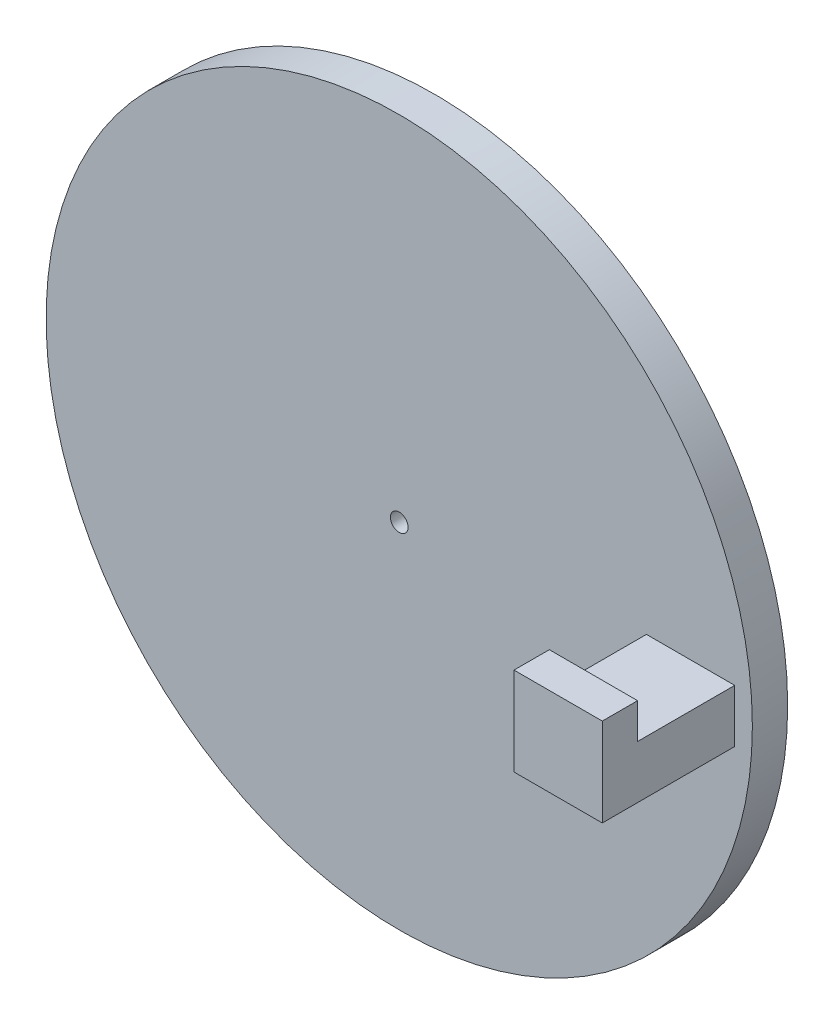
SolidWorks part; units mm, degrees
ref_plane "Front Plane" through (0, 0, 0) normal (0, 0, 1) x (1, 0, 0)
ref_plane "Top Plane" through (0, 0, 0) normal (0, 1, 0) x (1, 0, 0)
ref_plane "Right Plane" through (0, 0, 0) normal (1, 0, 0) x (0, 0, -1)
sketch "Sketch1" plane through (0, 0, 0) normal (0, 0, 1) x (1, 0, 0)
  circle A0 centre (0, 0) radius 50.8
  circle A1 centre (0, 0) radius 1.27
  dimension "D1" = 101.6
  dimension "D2" = 2.54
extrude "Boss-Extrude1" add sketch "Sketch1" along normal blind 5.08
sketch "Sketch2" plane through (0, 0, 5.08) normal (0, 0, 1) x (1, 0, 0)
  line L1 (35.56, -3.81) -> (48.26, -3.81)
  line L2 (35.56, -3.81) -> (35.56, 3.81)
  line L3 (35.56, 3.81) -> (48.26, 3.81)
  line L4 (48.26, -3.81) -> (48.26, 3.81)
  circle A1 centre (0, 0) radius 50.8 construction
  point P4 (35.56, 0)
  point P6 (49.8619, 4.2809)
  dimension "D1" = 12.7
  dimension "D2" = 7.62
  dimension "D3" = 48.26
extrude "Boss-Extrude2" add sketch "Sketch2" along normal blind 19.05
sketch "Sketch3" plane through (0, 3.81, 0) normal (0, 1, 0) x (1, 0, 0)
  line L0 (48.26, -24.13) -> (48.26, -5.08) construction
  line L1 (35.56, -24.13) -> (48.26, -24.13)
  line L2 (35.56, -24.13) -> (35.56, -19.05)
  line L3 (35.56, -19.05) -> (48.26, -19.05)
  line L4 (48.26, -24.13) -> (48.26, -19.05)
  dimension "D1" = 5.08
extrude "Boss-Extrude3" add sketch "Sketch3" along normal blind 5.08
